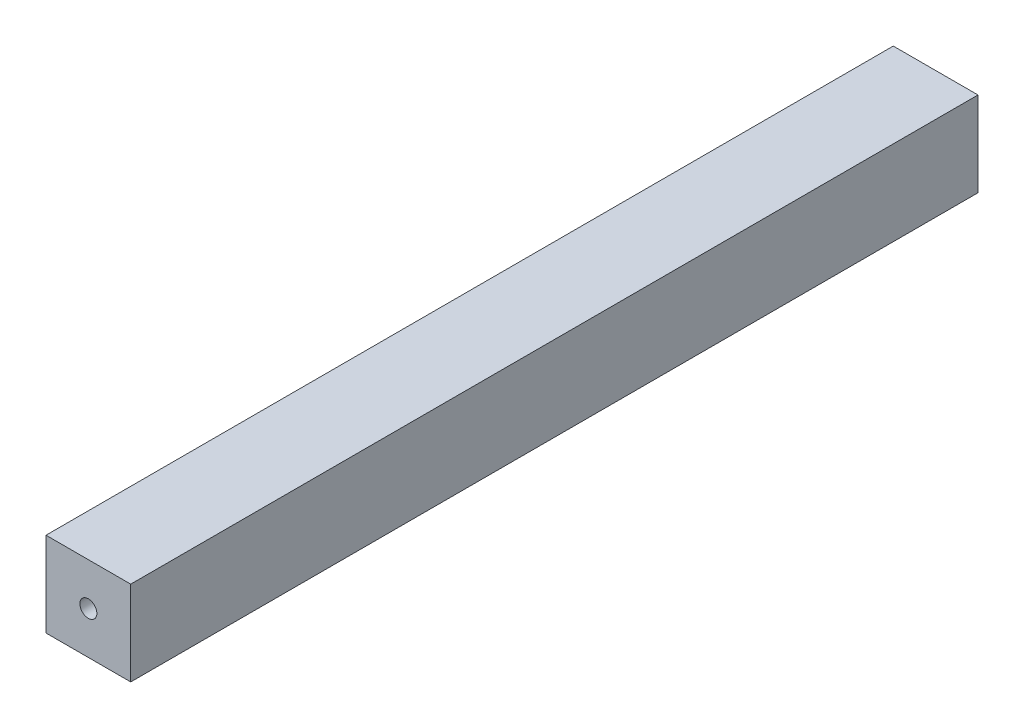
SolidWorks part; units mm, degrees
ref_plane "Plan de face" through (0, 0, 0) normal (0, 0, 1) x (1, 0, 0)
ref_plane "Plan de dessus" through (0, 0, 0) normal (0, 1, 0) x (1, 0, 0)
ref_plane "Plan de droite" through (0, 0, 0) normal (1, 0, 0) x (0, 0, -1)
sketch "Esquisse1" plane through (0, 0, 0) normal (0, 0, 1) x (1, 0, 0)
  line L0 (12.5, 12.5) -> (-12.5, -12.5) construction
  line L1 (-12.5, 12.5) -> (12.5, 12.5)
  line L2 (-12.5, 12.5) -> (-12.5, -12.5)
  line L3 (-12.5, -12.5) -> (12.5, -12.5)
  line L4 (12.5, 12.5) -> (12.5, -12.5)
  line L5 (-12.5, 12.5) -> (12.5, -12.5) construction
  point P4 (0, 0)
  dimension "D1" = 25
  dimension "D2" = 25
extrude "Boss.-Extru.1" add sketch "Esquisse1" along normal blind 250
sketch "Esquisse2" plane through (0, 0, 0) normal (0, 0, 1) x (1, 0, 0)
  line L0 (-12.5, 12.5) -> (12.5, -12.5) construction
  circle A0 centre (0, 0) radius 2.5
  dimension "D1" = 5
extrude "Enlèv. mat.-Extru.3" cut sketch "Esquisse2" along normal blind 250
